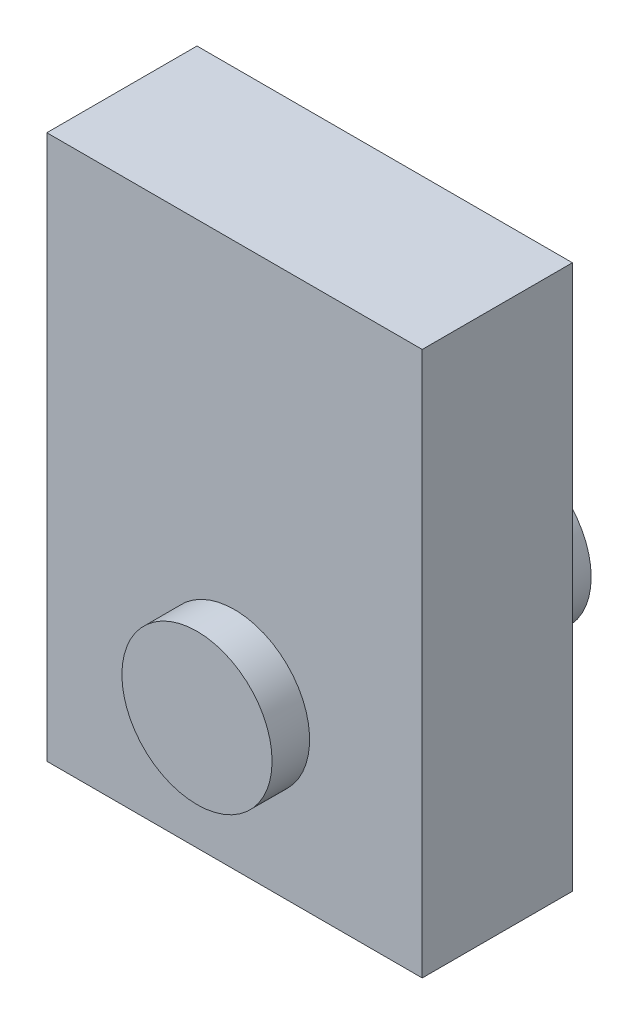
SolidWorks part; units mm, degrees
ref_plane "Front Plane" through (0, 0, 0) normal (0, 0, 1) x (1, 0, 0)
ref_plane "Top Plane" through (0, 0, 0) normal (0, 1, 0) x (1, 0, 0)
ref_plane "Right Plane" through (0, 0, 0) normal (1, 0, 0) x (0, 0, -1)
sketch "SK_P01_Hanger" plane through (0, 0, 0) normal (0, 1, 0) x (1, 0, 0)
  line L0 (-10, -6.5) -> (10, -6.5)
  line L1 (10, -6.5) -> (10, 1.5)
  line L2 (10, 1.5) -> (-10, 1.5)
  line L3 (-10, 1.5) -> (-10, -6.5)
extrude "P01_Hanger" add sketch "SK_P01_Hanger" along normal blind 29
sketch "SK_P02_Pivotpin8mm" plane through (0, 0, 0) normal (0, 0, 1) x (1, 0, 0)
  circle A0 centre (0, 8) radius 4
extrude "P02_Pivotpin8mm" add sketch "SK_P02_Pivotpin8mm" along normal blind 17 from offset 8.5
